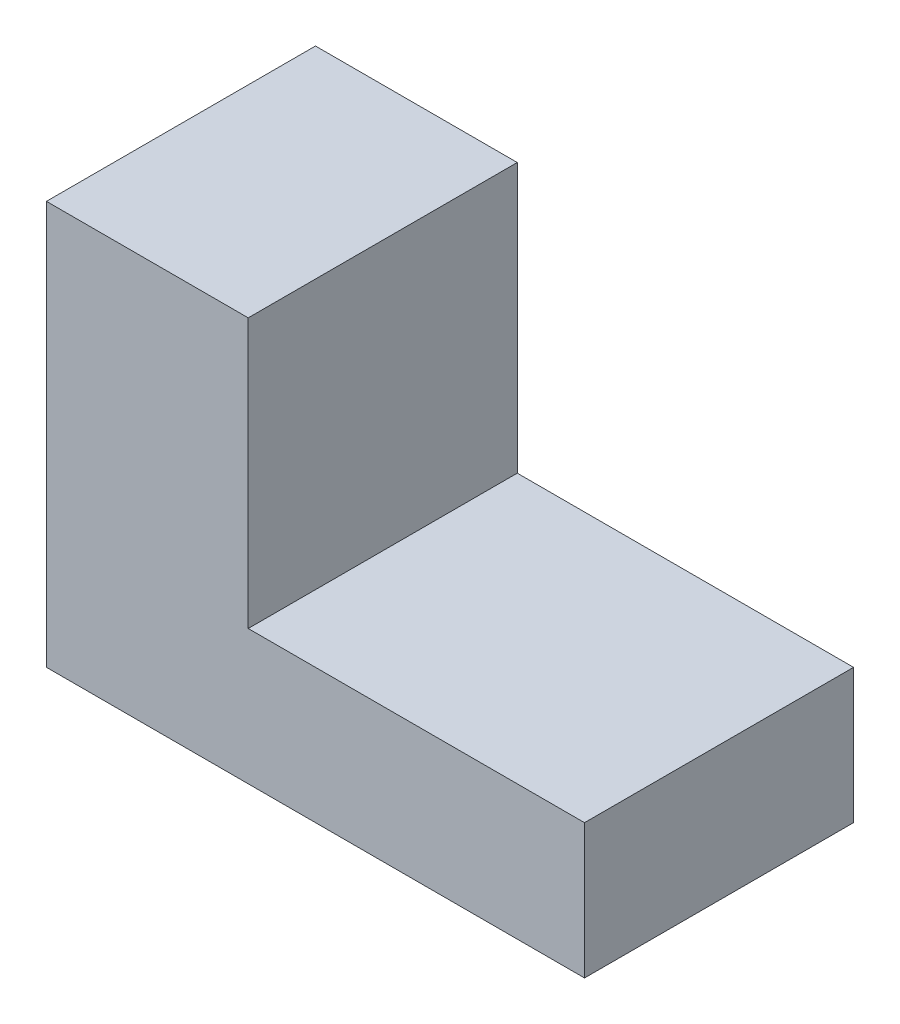
SolidWorks part; units mm, degrees
ref_plane "Front Plane" through (0, 0, 0) normal (0, 0, 1) x (1, 0, 0)
ref_plane "Top Plane" through (0, 0, 0) normal (0, 1, 0) x (1, 0, 0)
ref_plane "Right Plane" through (0, 0, 0) normal (1, 0, 0) x (0, 0, -1)
ref_plane "plane:base-xy" through (0, 0, 0) normal (0, 0, 1) x (1, 0, 0)
sketch "sketch:main-profile" plane through (0, 0, 0) normal (0, 0, 1) x (1, 0, 0)
  line L0 (0, 0) -> (40, 0)
  line L1 (40, 0) -> (40, 10)
  line L2 (40, 10) -> (15, 10)
  line L3 (15, 10) -> (15, 30)
  line L4 (15, 30) -> (0, 30)
  line L5 (0, 30) -> (0, 0)
extrude "feature:base" add sketch "sketch:main-profile" along normal blind 20 separate body
